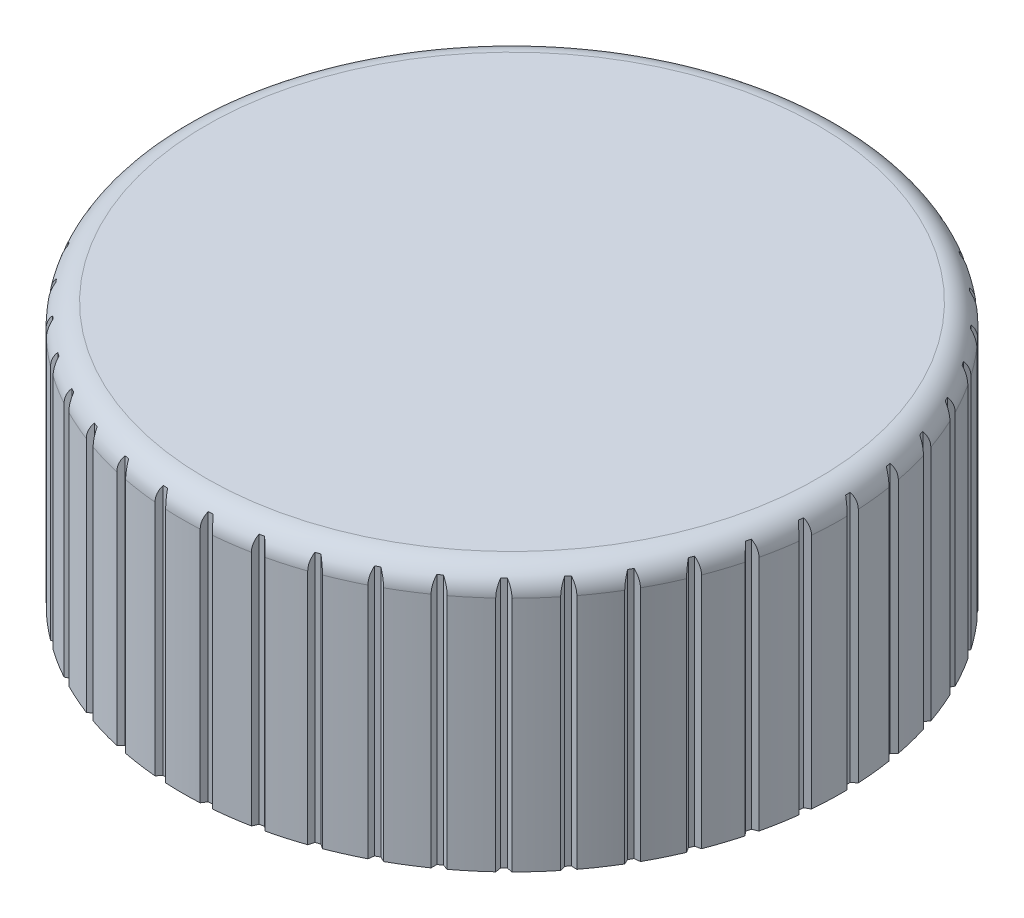
SolidWorks part; units mm, degrees
ref_plane "Front Plane" through (0, 0, 0) normal (0, 0, 1) x (1, 0, 0)
ref_plane "Top Plane" through (0, 0, 0) normal (0, 1, 0) x (1, 0, 0)
ref_plane "Right Plane" through (0, 0, 0) normal (1, 0, 0) x (0, 0, -1)
sketch "草图1" plane through (0, 0, 0) normal (0, 1, 0) x (1, 0, 0)
  circle A0 centre (0, 0) radius 13.9
extrude "凸台-拉伸1" add sketch "草图1" along normal blind 11
sketch "草图2" plane through (0, 0, 0) normal (0, -1, 0) x (1, 0, 0)
  circle A0 centre (0, 0) radius 2.95
extrude "切除-拉伸1" cut sketch "草图2" against normal blind 8.8
fillet "圆角1" radius 1 1 edges at (0, 11, 13.9)
sketch "草图3" plane through (0, 0, 0) normal (0, -1, 0) x (1, 0, 0)
  line L0 (4.8479, -1) -> (11.8579, -1)
  line L1 (1, 4.8479) -> (1, 11.8579)
  line L2 (-1, 4.8479) -> (-1, 11.8579)
  line L3 (4.8479, 1) -> (11.8579, 1)
  line L4 (-1, -4.8479) -> (-1, -11.8579)
  line L5 (1, -4.8479) -> (1, -11.8579)
  line L6 (-4.8479, 1) -> (-11.8579, 1)
  line L7 (-4.8479, -1) -> (-11.8579, -1)
  arc A1 (-4.8479, -1) -> (-1, -4.8479) centre (0, 0) ccw
  arc A4 (-11.8579, -1) -> (-1, -11.8579) centre (0, 0) ccw
  arc A5 (-1, 4.8479) -> (-4.8479, 1) centre (0, 0) ccw
  arc A6 (4.8479, 1) -> (1, 4.8479) centre (0, 0) ccw
  arc A7 (1, -4.8479) -> (4.8479, -1) centre (0, 0) ccw
  arc A8 (1, -11.8579) -> (11.8579, -1) centre (0, 0) ccw
  arc A9 (11.8579, 1) -> (1, 11.8579) centre (0, 0) ccw
  arc A10 (-1, 11.8579) -> (-11.8579, 1) centre (0, 0) ccw
  point P0 (1, 0)
  point P1 (0, 11.9)
  point P4 (1, 11.9)
  point P5 (-1, 0)
  point P8 (-1, 11.9)
  dimension "D1" = 4
extrude "切除-拉伸2" cut sketch "草图3" against normal blind 9
sketch "草图5" plane through (0, 11, 0) normal (0, 1, 0) x (1, 0, 0)
  line L2 (1.9067, 13.5667) -> (1.8076, 13.5806)
  line L3 (0, 13.7) -> (-0.1, 13.7)
  line L4 (0, 13.7) -> (0.1, 13.7)
  line L5 (-0.1, 13.7) -> (-0.2426, 13.8979)
  line L6 (0.1, 13.7) -> (0.2426, 13.8979)
  line L7 (1.9067, 13.5667) -> (2.0057, 13.5528)
  line L8 (1.8076, 13.5806) -> (1.694, 13.7964)
  line L9 (2.0057, 13.5528) -> (2.1744, 13.7289)
  line L10 (3.7762, 13.1693) -> (3.6801, 13.1968)
  line L11 (3.7762, 13.1693) -> (3.8724, 13.1417)
  line L12 (3.6801, 13.1968) -> (3.5976, 13.4264)
  line L13 (3.8724, 13.1417) -> (4.064, 13.2926)
  line L14 (5.5723, 12.5156) -> (5.4809, 12.5562)
  line L15 (5.5723, 12.5156) -> (5.6636, 12.4749)
  line L16 (5.4809, 12.5562) -> (5.4312, 12.795)
  line L17 (5.6636, 12.4749) -> (5.8744, 12.5977)
  line L18 (7.2599, 11.6183) -> (7.1751, 11.6713)
  line L19 (7.2599, 11.6183) -> (7.3447, 11.5653)
  line L20 (7.1751, 11.6713) -> (7.159, 11.9146)
  line L21 (7.3447, 11.5653) -> (7.5705, 11.6575)
  line L22 (8.8062, 10.4948) -> (8.7296, 10.5591)
  line L23 (8.8062, 10.4948) -> (8.8828, 10.4305)
  line L24 (8.7296, 10.5591) -> (8.7476, 10.8023)
  line L25 (8.8828, 10.4305) -> (9.1192, 10.4905)
  line L26 (10.1811, 9.1671) -> (10.1142, 9.2414)
  line L27 (10.1811, 9.1671) -> (10.248, 9.0928)
  line L28 (10.1142, 9.2414) -> (10.1658, 9.4798)
  line L29 (10.248, 9.0928) -> (10.4905, 9.1192)
  line L30 (11.3578, 7.6609) -> (11.3019, 7.7438)
  line L31 (11.3578, 7.6609) -> (11.4137, 7.578)
  line L32 (11.3019, 7.7438) -> (11.3862, 7.9727)
  line L33 (11.4137, 7.578) -> (11.6575, 7.5705)
  line L34 (12.3135, 6.0057) -> (12.2696, 6.0956)
  line L35 (12.3135, 6.0057) -> (12.3573, 5.9158)
  line L36 (12.2696, 6.0956) -> (12.385, 6.3105)
  line L37 (12.3573, 5.9158) -> (12.5977, 5.8744)
  line L38 (13.0295, 4.2335) -> (12.9986, 4.3286)
  line L39 (13.0295, 4.2335) -> (13.0604, 4.1384)
  line L40 (12.9986, 4.3286) -> (13.1427, 4.5254)
  line L41 (13.0604, 4.1384) -> (13.2926, 4.064)
  line L42 (13.4919, 2.379) -> (13.4745, 2.4775)
  line L43 (13.4919, 2.379) -> (13.5092, 2.2805)
  line L44 (13.4745, 2.4775) -> (13.6446, 2.6522)
  line L45 (13.5092, 2.2805) -> (13.7289, 2.1744)
  line L46 (13.6917, 0.4781) -> (13.6882, 0.5781)
  line L47 (13.6917, 0.4781) -> (13.6951, 0.3782)
  line L48 (13.6882, 0.5781) -> (13.881, 0.7275)
  line L49 (13.6951, 0.3782) -> (13.8979, 0.2426)
  line L50 (13.6249, -1.432) -> (13.6354, -1.3326)
  line L51 (13.6249, -1.432) -> (13.6145, -1.5315)
  line L52 (13.6354, -1.3326) -> (13.8471, -1.2115)
  line L53 (13.6145, -1.5315) -> (13.7964, -1.694)
  line L54 (13.2931, -3.3143) -> (13.3172, -3.2173)
  line L55 (13.2931, -3.3143) -> (13.2689, -3.4114)
  line L56 (13.3172, -3.2173) -> (13.5437, -3.1268)
  line L57 (13.2689, -3.4114) -> (13.4264, -3.5976)
  line L58 (12.7024, -5.1321) -> (12.7399, -5.0394)
  line L59 (12.7024, -5.1321) -> (12.665, -5.2248)
  line L60 (12.7399, -5.0394) -> (12.9768, -4.9813)
  line L61 (12.665, -5.2248) -> (12.795, -5.4312)
  line L62 (11.8645, -6.85) -> (11.9145, -6.7634)
  line L63 (11.8645, -6.85) -> (11.8145, -6.9366)
  line L64 (11.9145, -6.7634) -> (12.1572, -6.7389)
  line L65 (11.8145, -6.9366) -> (11.9146, -7.159)
  line L66 (10.7957, -8.4346) -> (10.8573, -8.3558)
  line L67 (10.7957, -8.4346) -> (10.7342, -8.5134)
  line L68 (10.8573, -8.3558) -> (11.101, -8.3652)
  line L69 (10.7342, -8.5134) -> (10.8023, -8.7476)
  line L70 (9.5168, -9.855) -> (9.5888, -9.7855)
  line L71 (9.5168, -9.855) -> (9.4449, -9.9244)
  line L72 (9.5888, -9.7855) -> (9.8288, -9.8288)
  line L73 (9.4449, -9.9244) -> (9.4798, -10.1658)
  line L74 (8.0527, -11.0835) -> (8.1336, -11.0248)
  line L75 (8.0527, -11.0835) -> (7.9718, -11.1423)
  line L76 (8.1336, -11.0248) -> (8.3652, -11.101)
  line L77 (7.9718, -11.1423) -> (7.9727, -11.3862)
  line L78 (6.4318, -12.0964) -> (6.5201, -12.0494)
  line L79 (6.4318, -12.0964) -> (6.3435, -12.1433)
  line L80 (6.5201, -12.0494) -> (6.7389, -12.1572)
  line L81 (6.3435, -12.1433) -> (6.3105, -12.385)
  line L82 (4.6857, -12.8738) -> (4.7796, -12.8396)
  line L83 (4.6857, -12.8738) -> (4.5917, -12.908)
  line L84 (4.7796, -12.8396) -> (4.9813, -12.9768)
  line L85 (4.5917, -12.908) -> (4.5254, -13.1427)
  line L86 (2.8484, -13.4006) -> (2.9462, -13.3798)
  line L87 (2.8484, -13.4006) -> (2.7506, -13.4214)
  line L88 (2.9462, -13.3798) -> (3.1268, -13.5437)
  line L89 (2.7506, -13.4214) -> (2.6522, -13.6446)
  line L90 (0.9557, -13.6666) -> (1.0554, -13.6597)
  line L91 (0.9557, -13.6666) -> (0.8559, -13.6736)
  line L92 (1.0554, -13.6597) -> (1.2115, -13.8471)
  line L93 (0.8559, -13.6736) -> (0.7275, -13.881)
  line L94 (-0.9557, -13.6666) -> (-0.8559, -13.6736)
  line L95 (-0.9557, -13.6666) -> (-1.0554, -13.6597)
  line L96 (-0.8559, -13.6736) -> (-0.7275, -13.881)
  line L97 (-1.0554, -13.6597) -> (-1.2115, -13.8471)
  line L98 (-2.8484, -13.4006) -> (-2.7506, -13.4214)
  line L99 (-2.8484, -13.4006) -> (-2.9462, -13.3798)
  line L100 (-2.7506, -13.4214) -> (-2.6522, -13.6446)
  line L101 (-2.9462, -13.3798) -> (-3.1268, -13.5437)
  line L102 (-4.6857, -12.8738) -> (-4.5917, -12.908)
  line L103 (-4.6857, -12.8738) -> (-4.7796, -12.8396)
  line L104 (-4.5917, -12.908) -> (-4.5254, -13.1427)
  line L105 (-4.7796, -12.8396) -> (-4.9813, -12.9768)
  line L106 (-6.4318, -12.0964) -> (-6.3435, -12.1433)
  line L107 (-6.4318, -12.0964) -> (-6.5201, -12.0494)
  line L108 (-6.3435, -12.1433) -> (-6.3105, -12.385)
  line L109 (-6.5201, -12.0494) -> (-6.7389, -12.1572)
  line L110 (-8.0527, -11.0835) -> (-7.9718, -11.1423)
  line L111 (-8.0527, -11.0835) -> (-8.1336, -11.0248)
  line L112 (-7.9718, -11.1423) -> (-7.9727, -11.3862)
  line L113 (-8.1336, -11.0248) -> (-8.3652, -11.101)
  line L114 (-9.5168, -9.855) -> (-9.4449, -9.9244)
  line L115 (-9.5168, -9.855) -> (-9.5888, -9.7855)
  line L116 (-9.4449, -9.9244) -> (-9.4798, -10.1658)
  line L117 (-9.5888, -9.7855) -> (-9.8288, -9.8288)
  line L118 (-10.7957, -8.4346) -> (-10.7342, -8.5134)
  line L119 (-10.7957, -8.4346) -> (-10.8573, -8.3558)
  line L120 (-10.7342, -8.5134) -> (-10.8023, -8.7476)
  line L121 (-10.8573, -8.3558) -> (-11.101, -8.3652)
  line L122 (-11.8645, -6.85) -> (-11.8145, -6.9366)
  line L123 (-11.8645, -6.85) -> (-11.9145, -6.7634)
  line L124 (-11.8145, -6.9366) -> (-11.9146, -7.159)
  line L125 (-11.9145, -6.7634) -> (-12.1572, -6.7389)
  line L126 (-12.7024, -5.1321) -> (-12.665, -5.2248)
  line L127 (-12.7024, -5.1321) -> (-12.7399, -5.0394)
  line L128 (-12.665, -5.2248) -> (-12.795, -5.4312)
  line L129 (-12.7399, -5.0394) -> (-12.9768, -4.9813)
  line L130 (-13.2931, -3.3143) -> (-13.2689, -3.4114)
  line L131 (-13.2931, -3.3143) -> (-13.3172, -3.2173)
  line L132 (-13.2689, -3.4114) -> (-13.4264, -3.5976)
  line L133 (-13.3172, -3.2173) -> (-13.5437, -3.1268)
  line L134 (-13.6249, -1.432) -> (-13.6145, -1.5315)
  line L135 (-13.6249, -1.432) -> (-13.6354, -1.3326)
  line L136 (-13.6145, -1.5315) -> (-13.7964, -1.694)
  line L137 (-13.6354, -1.3326) -> (-13.8471, -1.2115)
  line L138 (-13.6917, 0.4781) -> (-13.6951, 0.3782)
  line L139 (-13.6917, 0.4781) -> (-13.6882, 0.5781)
  line L140 (-13.6951, 0.3782) -> (-13.8979, 0.2426)
  line L141 (-13.6882, 0.5781) -> (-13.881, 0.7275)
  line L142 (-13.4919, 2.379) -> (-13.5092, 2.2805)
  line L143 (-13.4919, 2.379) -> (-13.4745, 2.4775)
  line L144 (-13.5092, 2.2805) -> (-13.7289, 2.1744)
  line L145 (-13.4745, 2.4775) -> (-13.6446, 2.6522)
  line L146 (-13.0295, 4.2335) -> (-13.0604, 4.1384)
  line L147 (-13.0295, 4.2335) -> (-12.9986, 4.3286)
  line L148 (-13.0604, 4.1384) -> (-13.2926, 4.064)
  line L149 (-12.9986, 4.3286) -> (-13.1427, 4.5254)
  line L150 (-12.3135, 6.0057) -> (-12.3573, 5.9158)
  line L151 (-12.3135, 6.0057) -> (-12.2696, 6.0956)
  line L152 (-12.3573, 5.9158) -> (-12.5977, 5.8744)
  line L153 (-12.2696, 6.0956) -> (-12.385, 6.3105)
  line L154 (-11.3578, 7.6609) -> (-11.4137, 7.578)
  line L155 (-11.3578, 7.6609) -> (-11.3019, 7.7438)
  line L156 (-11.4137, 7.578) -> (-11.6575, 7.5705)
  line L157 (-11.3019, 7.7438) -> (-11.3862, 7.9727)
  line L158 (-10.1811, 9.1671) -> (-10.248, 9.0928)
  line L159 (-10.1811, 9.1671) -> (-10.1142, 9.2414)
  line L160 (-10.248, 9.0928) -> (-10.4905, 9.1192)
  line L161 (-10.1142, 9.2414) -> (-10.1658, 9.4798)
  line L162 (-8.8062, 10.4948) -> (-8.8828, 10.4305)
  line L163 (-8.8062, 10.4948) -> (-8.7296, 10.5591)
  line L164 (-8.8828, 10.4305) -> (-9.1192, 10.4905)
  line L165 (-8.7296, 10.5591) -> (-8.7476, 10.8023)
  line L166 (-7.2599, 11.6183) -> (-7.3447, 11.5653)
  line L167 (-7.2599, 11.6183) -> (-7.1751, 11.6713)
  line L168 (-7.3447, 11.5653) -> (-7.5705, 11.6575)
  line L169 (-7.1751, 11.6713) -> (-7.159, 11.9146)
  line L170 (-5.5723, 12.5156) -> (-5.6636, 12.4749)
  line L171 (-5.5723, 12.5156) -> (-5.4809, 12.5562)
  line L172 (-5.6636, 12.4749) -> (-5.8744, 12.5977)
  line L173 (-5.4809, 12.5562) -> (-5.4312, 12.795)
  line L174 (-3.7762, 13.1693) -> (-3.8724, 13.1417)
  line L175 (-3.7762, 13.1693) -> (-3.6801, 13.1968)
  line L176 (-3.8724, 13.1417) -> (-4.064, 13.2926)
  line L177 (-3.6801, 13.1968) -> (-3.5976, 13.4264)
  line L178 (-1.9067, 13.5667) -> (-2.0057, 13.5528)
  line L179 (-1.9067, 13.5667) -> (-1.8076, 13.5806)
  line L180 (-2.0057, 13.5528) -> (-2.1744, 13.7289)
  line L181 (-1.8076, 13.5806) -> (-1.694, 13.7964)
  circle A0 centre (0, 0) radius 13.9 construction
  arc A1 (0.2426, 13.8979) -> (-0.2426, 13.8979) centre (0, 0) ccw
  arc A2 (2.1744, 13.7289) -> (1.694, 13.7964) centre (0, 0) ccw
  arc A3 (4.064, 13.2926) -> (3.5976, 13.4264) centre (0, 0) ccw
  arc A4 (5.8744, 12.5977) -> (5.4312, 12.795) centre (0, 0) ccw
  arc A5 (7.5705, 11.6575) -> (7.159, 11.9146) centre (0, 0) ccw
  arc A6 (9.1192, 10.4905) -> (8.7476, 10.8023) centre (0, 0) ccw
  arc A7 (10.4905, 9.1192) -> (10.1658, 9.4798) centre (0, 0) ccw
  arc A8 (11.6575, 7.5705) -> (11.3862, 7.9727) centre (0, 0) ccw
  arc A9 (12.5977, 5.8744) -> (12.385, 6.3105) centre (0, 0) ccw
  arc A10 (13.2926, 4.064) -> (13.1427, 4.5254) centre (0, 0) ccw
  arc A11 (13.7289, 2.1744) -> (13.6446, 2.6522) centre (0, 0) ccw
  arc A12 (13.8979, 0.2426) -> (13.881, 0.7275) centre (0, 0) ccw
  arc A13 (13.7964, -1.694) -> (13.8471, -1.2115) centre (0, 0) ccw
  arc A14 (13.4264, -3.5976) -> (13.5437, -3.1268) centre (0, 0) ccw
  arc A15 (12.795, -5.4312) -> (12.9768, -4.9813) centre (0, 0) ccw
  arc A16 (11.9146, -7.159) -> (12.1572, -6.7389) centre (0, 0) ccw
  arc A17 (10.8023, -8.7476) -> (11.101, -8.3652) centre (0, 0) ccw
  arc A18 (9.4798, -10.1658) -> (9.8288, -9.8288) centre (0, 0) ccw
  arc A19 (7.9727, -11.3862) -> (8.3652, -11.101) centre (0, 0) ccw
  arc A20 (6.3105, -12.385) -> (6.7389, -12.1572) centre (0, 0) ccw
  arc A21 (4.5254, -13.1427) -> (4.9813, -12.9768) centre (0, 0) ccw
  arc A22 (2.6522, -13.6446) -> (3.1268, -13.5437) centre (0, 0) ccw
  arc A23 (0.7275, -13.881) -> (1.2115, -13.8471) centre (0, 0) ccw
  arc A24 (-1.2115, -13.8471) -> (-0.7275, -13.881) centre (0, 0) ccw
  arc A25 (-3.1268, -13.5437) -> (-2.6522, -13.6446) centre (0, 0) ccw
  arc A26 (-4.9813, -12.9768) -> (-4.5254, -13.1427) centre (0, 0) ccw
  arc A27 (-6.7389, -12.1572) -> (-6.3105, -12.385) centre (0, 0) ccw
  arc A28 (-8.3652, -11.101) -> (-7.9727, -11.3862) centre (0, 0) ccw
  arc A29 (-9.8288, -9.8288) -> (-9.4798, -10.1658) centre (0, 0) ccw
  arc A30 (-11.101, -8.3652) -> (-10.8023, -8.7476) centre (0, 0) ccw
  arc A31 (-12.1572, -6.7389) -> (-11.9146, -7.159) centre (0, 0) ccw
  arc A32 (-12.9768, -4.9813) -> (-12.795, -5.4312) centre (0, 0) ccw
  arc A33 (-13.5437, -3.1268) -> (-13.4264, -3.5976) centre (0, 0) ccw
  arc A34 (-13.8471, -1.2115) -> (-13.7964, -1.694) centre (0, 0) ccw
  arc A35 (-13.881, 0.7275) -> (-13.8979, 0.2426) centre (0, 0) ccw
  arc A36 (-13.6446, 2.6522) -> (-13.7289, 2.1744) centre (0, 0) ccw
  arc A37 (-13.1427, 4.5254) -> (-13.2926, 4.064) centre (0, 0) ccw
  arc A38 (-12.385, 6.3105) -> (-12.5977, 5.8744) centre (0, 0) ccw
  arc A39 (-11.3862, 7.9727) -> (-11.6575, 7.5705) centre (0, 0) ccw
  arc A40 (-10.1658, 9.4798) -> (-10.4905, 9.1192) centre (0, 0) ccw
  arc A41 (-8.7476, 10.8023) -> (-9.1192, 10.4905) centre (0, 0) ccw
  arc A42 (-7.159, 11.9146) -> (-7.5705, 11.6575) centre (0, 0) ccw
  arc A43 (-5.4312, 12.795) -> (-5.8744, 12.5977) centre (0, 0) ccw
  arc A44 (-3.5976, 13.4264) -> (-4.064, 13.2926) centre (0, 0) ccw
  arc A45 (-1.694, 13.7964) -> (-2.1744, 13.7289) centre (0, 0) ccw
  dimension "D1" = 45
extrude "切除-拉伸3" cut sketch "草图5" against normal through all
